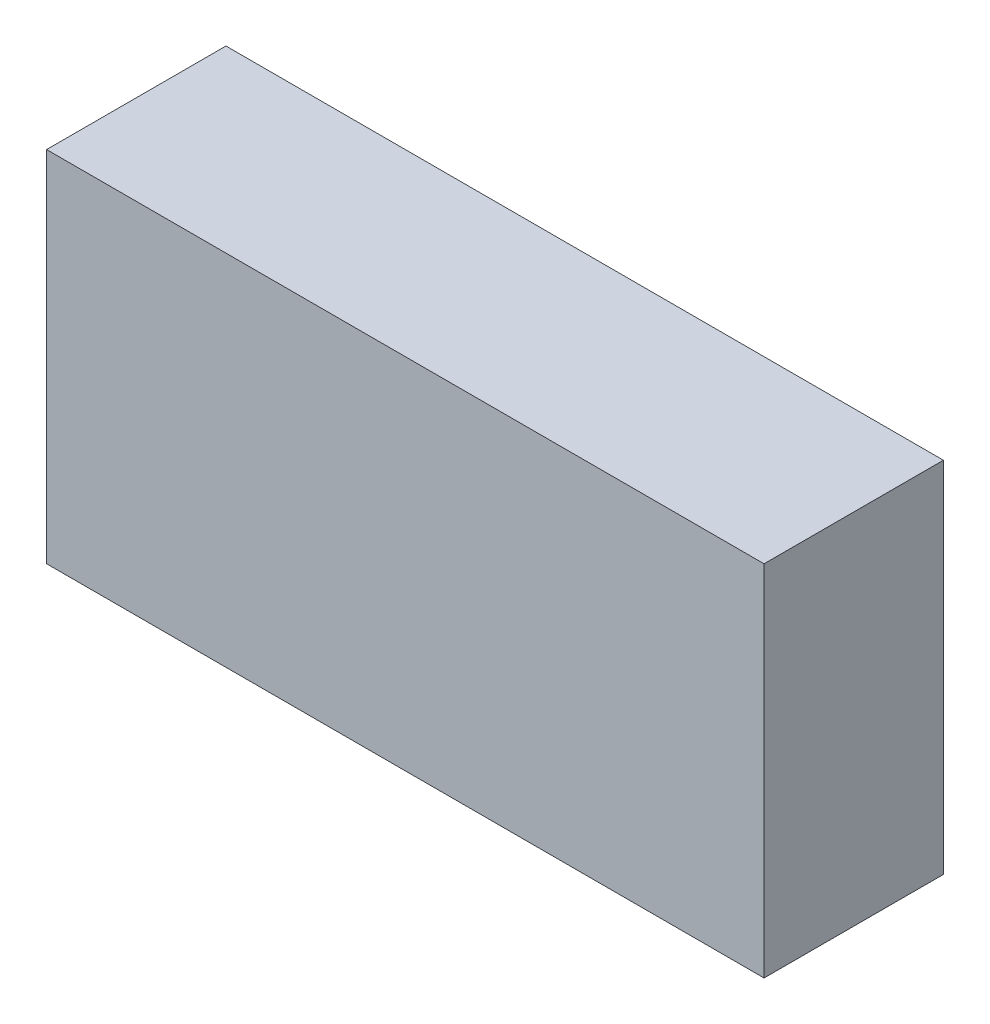
SolidWorks part; units mm, degrees
ref_plane "Plane1" through (0, 0, 0) normal (0, 0, 1) x (1, 0, 0)
ref_plane "Plane2" through (0, 0, 0) normal (0, 1, 0) x (1, 0, 0)
ref_plane "Plane3" through (0, 0, 0) normal (1, 0, 0) x (0, 0, -1)
sketch "Sketch1" plane through (0, 0, 0) normal (0, 0, 1) x (1, 0, 0)
  line L1 (0, 0) -> (203.2, 0)
  line L2 (0, 0) -> (0, 101.6)
  line L3 (0, 101.6) -> (203.2, 101.6)
  line L4 (203.2, 0) -> (203.2, 101.6)
  dimension "D1" = 203.2
  dimension "D2" = 101.6
extrude "Extrude1" add sketch "Sketch1" along normal blind 50.8
sketch "Sketch2" plane through (0, 0, 50.8) normal (0, 0, 1) x (1, 0, 0)
  line L0 (83.0232, 99.06) -> (89.3732, 99.06)
  line L2 (157.48, 83.82) -> (157.48, 78.74)
  line L3 (157.48, 78.74) -> (91.44, 78.74)
  line L4 (91.44, 78.74) -> (83.0232, 99.06)
  line L5 (203.2, 101.6) -> (0, 101.6) construction
  line L6 (0, 101.6) -> (0, 0) construction
  line L7 (157.48, 83.82) -> (102.4931, 88.7077)
  line L8 (98.7377, 90.3765) -> (89.3732, 99.06)
  arc A0 (98.7377, 90.3765) -> (102.4931, 88.7077) centre (103.0553, 95.0328) ccw
  point P12 (100.33, 88.9)
  dimension "D10" = 6.35
  dimension "D1" = 67.5
  dimension "D2" = 20.32
  dimension "D3" = 2.54
  dimension "D4" = 5.08
  dimension "D5" = 66.04
  dimension "D6" = 157.48
  dimension "D7" = 6.35
  dimension "D8" = 57.15
  dimension "D9" = 5.08
sketch "Sketch4" plane through (0, 0, 50.8) normal (0, 0, 1) x (1, 0, 0)
  line L0 (86.5799, 90.4733) -> (72.5, 84.6412)
  line L1 (91.44, 78.74) -> (83.0232, 99.06) construction
  line L2 (72.5, 84.6412) -> (69.6673, 84.8425)
  line L3 (69.6673, 84.8425) -> (73.0694, 76.6292)
  line L4 (73.0694, 76.6292) -> (74.93, 78.7745)
  line L5 (74.93, 78.7745) -> (89.01, 84.6066)
  line L6 (89.01, 84.6066) -> (91.8426, 84.4053)
  line L7 (91.8426, 84.4053) -> (88.4406, 92.6186)
  line L8 (88.4406, 92.6186) -> (86.5799, 90.4733)
  line L9 (79.54, 87.5572) -> (81.97, 81.6906)
  dimension "D1" = 6.35
  dimension "D2" = 8.89
  dimension "D3" = 1.27
  dimension "D4" = 8.89
  dimension "D5" = 1.27
  dimension "D6" = 2.54
  dimension "D7" = 2.54
  dimension "D8" = 15.24
  dimension "D9" = 6.35
sketch "Sketch5" plane through (0, 0, 50.8) normal (0, 0, 1) x (1, 0, 0)
  line L0 (69.7842, 91.1978) -> (77.5603, 72.4245)
  line L1 (77.5603, 72.4245) -> (43.4353, 38.2996)
  line L2 (43.4353, 38.2996) -> (23.4233, 51.0486)
  line L5 (23.4233, 51.0486) -> (30.1436, 56.8684)
  line L6 (157.48, 78.74) -> (91.44, 78.74) construction
  line L7 (30.1436, 56.8684) -> (37.6275, 52.1007)
  line L8 (45.5295, 52.9661) -> (64.4212, 71.8578)
  line L9 (65.7977, 78.778) -> (63.0639, 85.3779)
  line L10 (63.0639, 85.3779) -> (69.7842, 91.1978)
  arc A0 (37.6275, 52.1007) -> (45.5295, 52.9661) centre (41.0393, 57.4562) ccw
  arc A1 (65.7977, 78.778) -> (64.4212, 71.8578) centre (59.9311, 76.3479) cw
  point P14 (41.9258, 49.3624)
  dimension "D10" = 6.35
  dimension "D1" = 135
  dimension "D2" = 6.35
  dimension "D3" = 8.89
  dimension "D4" = 48.26
  dimension "D5" = 102.5
  dimension "D6" = 8.89
  dimension "D7" = 20.32
  dimension "D8" = 8.89
  dimension "D9" = 13.97
sketch "Sketch6" plane through (0, 0, 50.8) normal (0, 0, 1) x (1, 0, 0)
  line L0 (31.6531, 45.8056) -> (23.4647, 32.9524)
  line L1 (43.4353, 38.2996) -> (23.4233, 51.0486) construction
  line L2 (23.4647, 32.9524) -> (21.0288, 31.4925)
  line L3 (21.0288, 31.4925) -> (26.3844, 28.0807)
  line L4 (26.3844, 28.0807) -> (26.678, 30.9052)
  line L5 (26.678, 30.9052) -> (34.8665, 43.7585)
  line L6 (34.8665, 43.7585) -> (37.3023, 45.2184)
  line L7 (37.3023, 45.2184) -> (31.9468, 48.6302)
  line L8 (30.7722, 37.3319) -> (27.5589, 39.379)
  line L9 (31.9468, 48.6302) -> (31.6531, 45.8056)
  dimension "D1" = 3.81
  dimension "D2" = 6.35
  dimension "D3" = 6.35
  dimension "D4" = 1.27
  dimension "D5" = 1.27
  dimension "D6" = 2.54
  dimension "D7" = 2.54
  dimension "D8" = 15.24
  dimension "D9" = 10.16
sketch "Sketch8" plane through (0, 0, 50.8) normal (0, 0, 1) x (1, 0, 0)
  line L0 (16.648, 37.2951) -> (33.1047, 26.811)
  line L1 (33.1047, 26.811) -> (26.5892, 8.9099)
  line L2 (26.5892, 8.9099) -> (2.721, 17.5972)
  line L3 (16.648, 37.2951) -> (10.6809, 39.4669)
  line L4 (2.721, 17.5972) -> (10.6809, 39.4669)
  line L8 (43.4353, 38.2996) -> (23.4233, 51.0486) construction
  dimension "D1" = 7.62
  dimension "D2" = 102.5
  dimension "D3" = 25.4
  dimension "D4" = 19.05
  dimension "D5" = 6.35
sketch "Sketch14" plane through (0, 0, 50.8) normal (0, 0, 1) x (1, 0, 0)
  line L0 (157.48, 78.74) -> (91.44, 78.74) construction
  line L1 (93.98, 80.772) -> (154.94, 80.772)
  line L2 (93.98, 80.772) -> (93.98, 74.422)
  line L3 (93.98, 74.422) -> (154.94, 74.422)
  line L4 (154.94, 80.772) -> (154.94, 74.422)
  line L5 (157.48, 83.82) -> (157.48, 78.74) construction
  dimension "D1" = 2.032
  dimension "D2" = 2.54
  dimension "D3" = 2.54
  dimension "D4" = 6.35
sketch "Sketch15" plane through (0, 0, 50.8) normal (0, 0, 1) x (1, 0, 0)
  line L0 (43.7945, 41.5325) -> (48.2847, 37.0423)
  line L2 (48.2847, 37.0423) -> (78.8175, 67.5752)
  line L3 (78.8175, 67.5752) -> (74.3274, 72.0653)
  line L4 (74.3274, 72.0653) -> (43.7945, 41.5325)
  line L5 (77.5603, 72.4245) -> (43.4353, 38.2996) construction
  dimension "D1" = 2.032
  dimension "D2" = 2.54
  dimension "D3" = 6.35
  dimension "D4" = 2.54
sketch "Sketch16" plane through (0, 0, 50.8) normal (0, 0, 1) x (1, 0, 0)
  line L0 (25.5485, 11.9917) -> (31.5155, 9.8199)
  line L1 (31.5155, 9.8199) -> (36.2935, 22.9474)
  line L2 (36.2935, 22.9474) -> (30.3265, 25.1192)
  line L3 (30.3265, 25.1192) -> (25.5485, 11.9917)
  line L4 (33.1047, 26.811) -> (26.5892, 8.9099) construction
  dimension "D1" = 2.032
  dimension "D2" = 6.35
  dimension "D3" = 2.54
  dimension "D4" = 2.54
sketch "Sketch19" plane through (0, 0, 50.8) normal (0, 0, 1) x (1, 0, 0)
  line L0 (155.194, 72.39) -> (86.506, 72.39)
  line L1 (86.506, 72.39) -> (45.2314, 31.1154)
  line L2 (45.2314, 31.1154) -> (113.9194, 31.1154)
  line L3 (113.9194, 31.1154) -> (155.194, 72.39)
  line L4 (93.98, 74.422) -> (154.94, 74.422) construction
  line L5 (48.2847, 37.0423) -> (78.8175, 67.5752) construction
  line L7 (43.7945, 41.5325) -> (48.2847, 37.0423) construction
  line L8 (154.94, 80.772) -> (154.94, 74.422) construction
  dimension "D1" = 2.032
  dimension "D2" = 2.032
  dimension "D3" = 6.35
  dimension "D4" = 0.254
